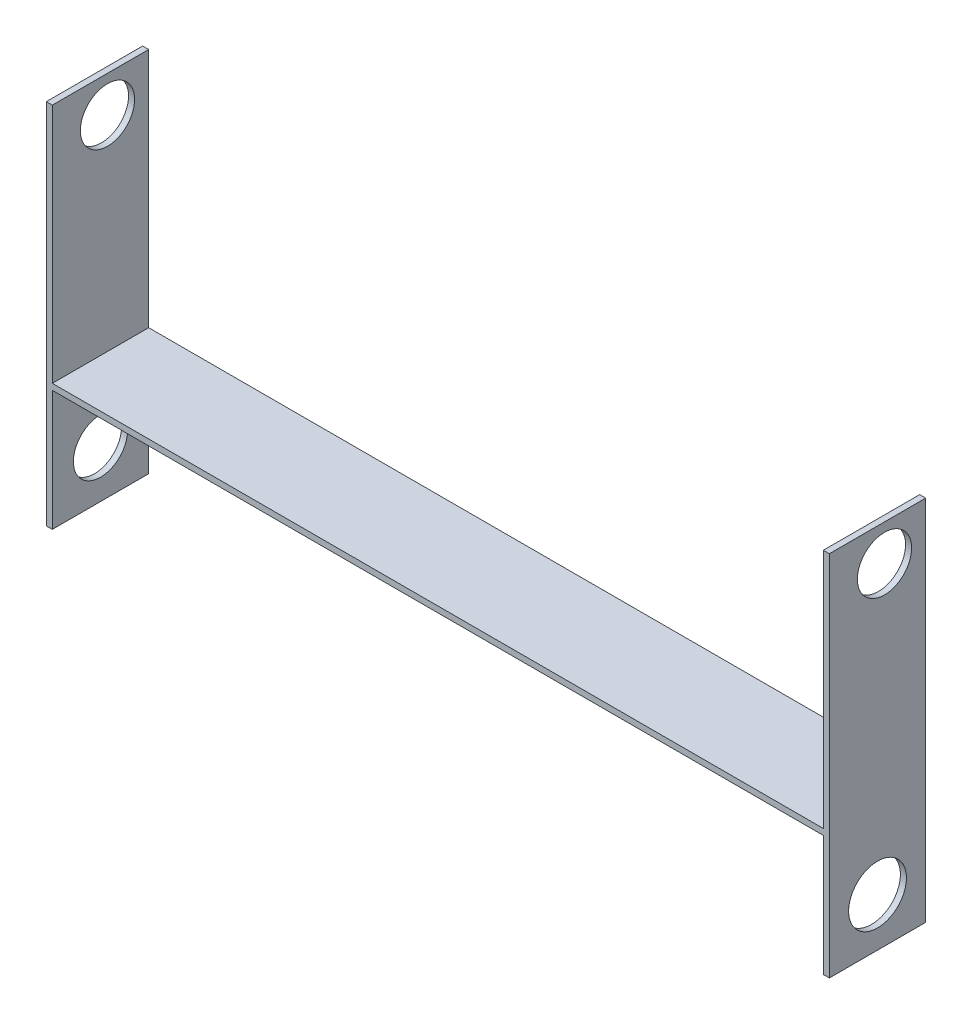
SolidWorks part; units mm, degrees
ref_plane "Front Plane" through (0, 0, 0) normal (0, 0, 1) x (1, 0, 0)
ref_plane "Top Plane" through (0, 0, 0) normal (0, 1, 0) x (1, 0, 0)
ref_plane "Right Plane" through (0, 0, 0) normal (1, 0, 0) x (0, 0, -1)
sketch "Sketch2" plane through (0, 0, 0) normal (0, 0, 1) x (1, 0, 0)
  line L0 (0, 0) -> (0, 130.175)
  line L1 (0, 130.175) -> (-3.175, 130.175)
  line L2 (-3.175, 130.175) -> (-3.175, 3.175)
  line L3 (-3.175, 3.175) -> (-409.575, 3.175)
  line L4 (-409.575, 3.175) -> (-409.575, 130.175)
  line L5 (-409.575, 130.175) -> (-412.75, 130.175)
  line L6 (-412.75, 130.175) -> (-412.75, 0)
  line L7 (-412.75, 0) -> (0, 0)
  dimension "D1" = 3.175
  dimension "D2" = 406.4
  dimension "D3" = 3.175
  dimension "D4" = 3.175
  dimension "D5" = 127
  dimension "D6" = 127
extrude "Boss-Extrude1" add sketch "Sketch2" along normal blind 50.8
sketch "Sketch3" plane through (-412.75, 0, 0) normal (-1, 0, 0) x (0, 0, 1)
  line L0 (50.8, 130.175) -> (50.8, 0) construction
  line L1 (0, 0) -> (50.8, 0)
  line L2 (0, 0) -> (0, -63.5)
  line L3 (0, -63.5) -> (50.8, -63.5)
  line L4 (50.8, 0) -> (50.8, -63.5)
  circle A0 centre (25.4, -38.1) radius 14.2875
  point P7 (25.4, -63.5)
  dimension "D3" = 28.575
  dimension "D1" = 63.5
  dimension "D2" = 25.4
  dimension "D4" = 25.4
  dimension "D5" = 0
extrude "Boss-Extrude2" add sketch "Sketch3" against normal blind 3.175
sketch "Sketch4" plane through (0, 0, 0) normal (1, 0, 0) x (0, 0, -1)
  line L0 (0, 0) -> (0, -63.5)
  line L1 (0, -63.5) -> (-50.8, -63.5)
  line L2 (-50.8, -63.5) -> (-50.8, 0)
  line L3 (-50.8, 0) -> (0, 0)
  circle A0 centre (-25.4, -38.1) radius 15.24
extrude "Boss-Extrude3" add sketch "Sketch4" against normal blind 3.175
sketch "Sketch5" plane through (0, 0, 0) normal (1, 0, 0) x (0, 0, -1)
  line L0 (0, -63.5) -> (0, 130.175) construction
  circle A0 centre (-21.7297, 111.125) radius 14.2875
  dimension "D1" = 28.575
  dimension "D2" = 21.7297
  dimension "D3" = 107.95
extrude "Cut-Extrude1" cut sketch "Sketch5" against normal blind 508
